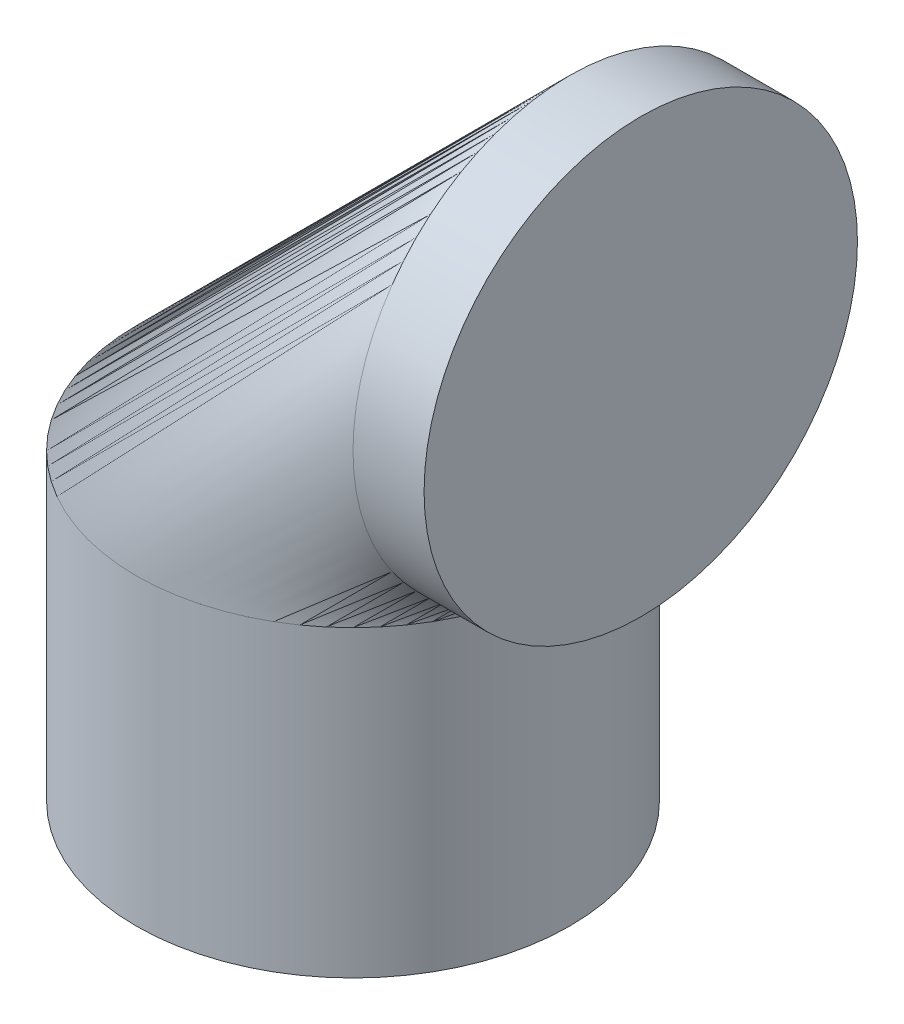
SolidWorks part; units mm, degrees
ref_plane "Front Plane" through (0, 0, 0) normal (0, 0, 1) x (1, 0, 0)
ref_plane "Top Plane" through (0, 0, 0) normal (0, 1, 0) x (1, 0, 0)
ref_plane "Right Plane" through (0, 0, 0) normal (1, 0, 0) x (0, 0, -1)
sketch "Sketch4" plane through (0, 0, 0) normal (0, 0, 1) x (1, 0, 0)
  line L0 (0, 0) -> (0, 35)
  line L1 (25, 60) -> (33.2, 60)
  arc A0 (0, 35) -> (25, 60) centre (25, 35) cw
  point P7 (0, 60)
  dimension "D3" = 25
  dimension "D1" = 60
  dimension "D2" = 33.2
sketch "Sketch5" plane through (0, 0, 0) normal (0, 1, 0) x (1, 0, 0)
  circle A0 centre (0, 0) radius 25
  dimension "D1" = 50
sweep "Sweep2" add profiles "Sketch5" path "Sketch4"
